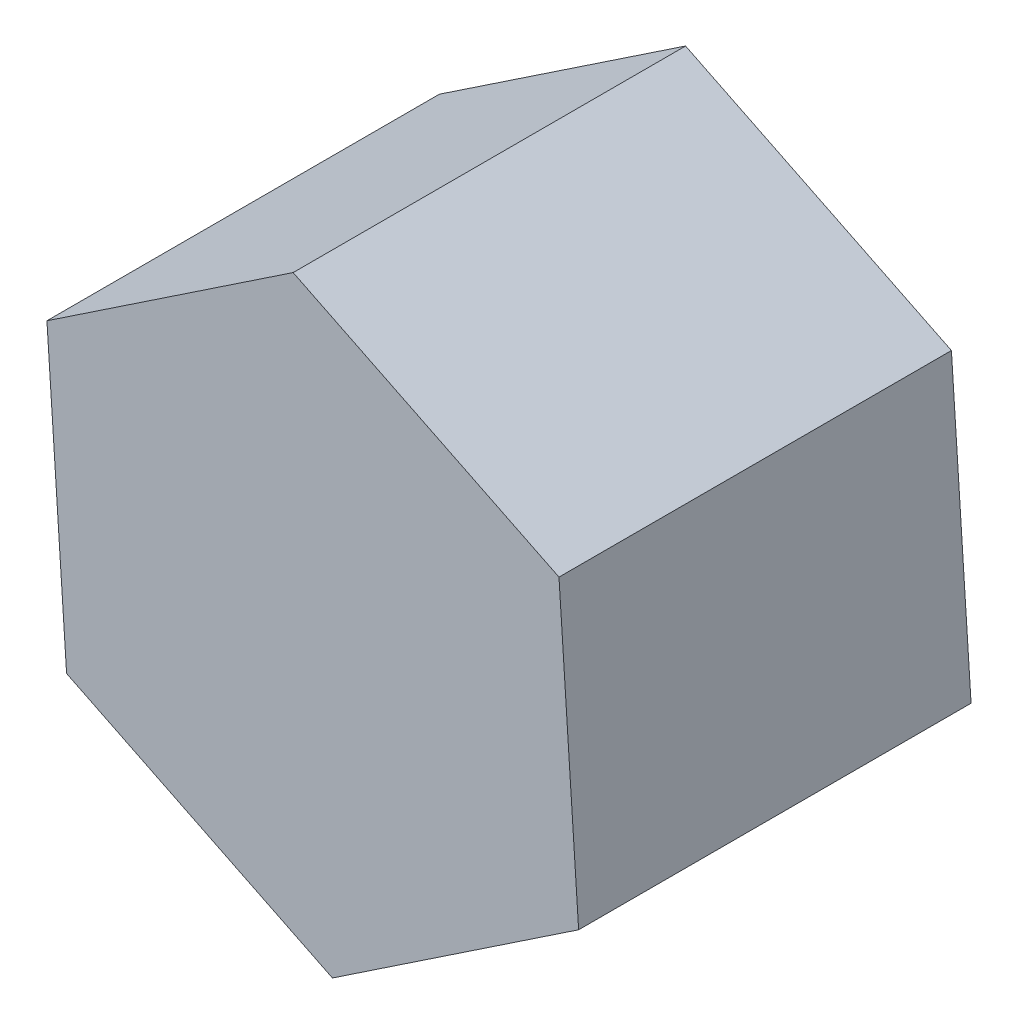
SolidWorks part; units mm, degrees
ref_plane "Front Plane" through (0, 0, 0) normal (0, 0, 1) x (1, 0, 0)
ref_plane "Top Plane" through (0, 0, 0) normal (0, 1, 0) x (1, 0, 0)
ref_plane "Right Plane" through (0, 0, 0) normal (1, 0, 0) x (0, 0, -1)
sketch "Sketch1" plane through (0, 0, 0) normal (0, 0, 1) x (1, 0, 0)
  line L1 (33.8723, -16.6652) -> (31.3686, 21.0017)
  line L2 (31.3686, 21.0017) -> (-2.5037, 37.6669)
  line L3 (-2.5037, 37.6669) -> (-33.8723, 16.6652)
  line L4 (-33.8723, 16.6652) -> (-31.3686, -21.0017)
  line L5 (-31.3686, -21.0017) -> (2.5037, -37.6669)
  line L6 (2.5037, -37.6669) -> (33.8723, -16.6652)
  circle A0 centre (0, 0) radius 32.6924 construction
extrude "Boss-Extrude1" add sketch "Sketch1" along normal blind 50
